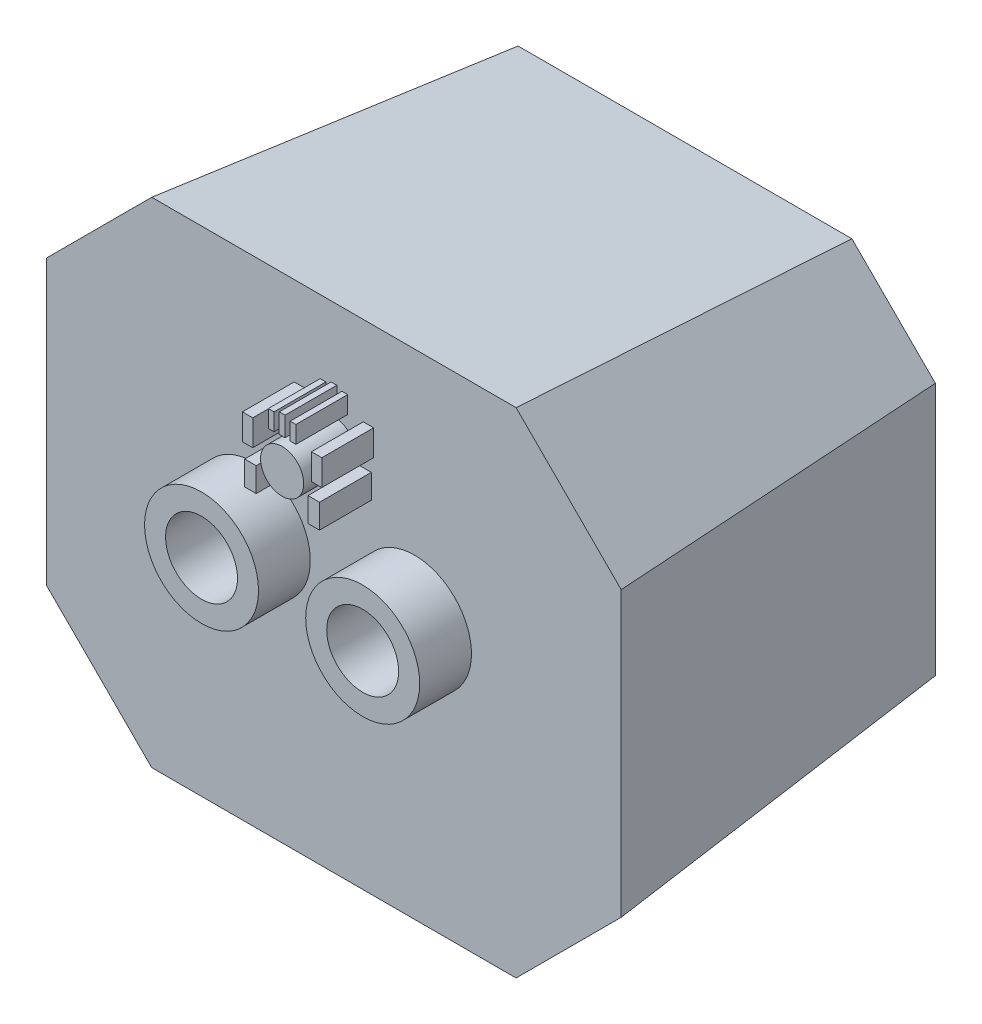
SolidWorks part; units mm, degrees
ref_plane "Front Plane" through (0, 0, 0) normal (0, 0, 1) x (1, 0, 0)
ref_plane "Top Plane" through (0, 0, 0) normal (0, 1, 0) x (1, 0, 0)
ref_plane "Right Plane" through (0, 0, 0) normal (1, 0, 0) x (0, 0, -1)
sketch "Sketch1" plane through (0, 0, 0) normal (0, 0, 1) x (1, 0, 0)
  line L0 (-58, 73) -> (58, 73)
  line L1 (58, 73) -> (87, 44)
  line L2 (87, 44) -> (87, -44)
  line L3 (87, -44) -> (58, -73)
  line L4 (58, -73) -> (-58, -73)
  line L5 (-58, -73) -> (-87, -44)
  line L6 (-87, -44) -> (-87, 44)
  line L7 (-87, 44) -> (-58, 73)
  circle A0 centre (-28, 4) radius 12.5
  circle A1 centre (28, 4) radius 12.5
extrude "Boss-Extrude1" add sketch "Sketch1" along normal blind 122 draft 6 draft outward yes
sketch "Sketch2" plane through (0, 0, 0) normal (0, 0, 1) x (1, 0, 0)
  line L1 (-4.8, 54.5) -> (-2.8, 54.5)
  line L2 (-4.8, 54.5) -> (-4.8, 60.5)
  line L3 (-4.8, 60.5) -> (-2.8, 60.5)
  line L4 (-2.8, 54.5) -> (-2.8, 60.5)
  line L6 (-1, 54.6) -> (1, 54.6)
  line L7 (-1, 54.6) -> (-1, 61.4)
  line L8 (-1, 61.4) -> (1, 61.4)
  line L9 (1, 54.6) -> (1, 61.4)
  line L11 (2.8, 54.5) -> (4.8, 54.5)
  line L12 (2.8, 54.5) -> (2.8, 60.5)
  line L13 (2.8, 60.5) -> (4.8, 60.5)
  line L14 (4.8, 54.5) -> (4.8, 60.5)
  line L16 (-13.8, 46) -> (-10.2, 46)
  line L17 (-13.8, 46) -> (-13.8, 55)
  line L18 (-13.8, 55) -> (-10.2, 55)
  line L19 (-10.2, 46) -> (-10.2, 55)
  line L21 (10.2, 46) -> (13.8, 46)
  line L22 (10.2, 46) -> (10.2, 55)
  line L23 (10.2, 55) -> (13.8, 55)
  line L24 (13.8, 46) -> (13.8, 55)
  line L26 (-13, 32.8) -> (-9, 32.8)
  line L27 (-13, 32.8) -> (-13, 41.2)
  line L28 (-13, 41.2) -> (-9, 41.2)
  line L29 (-9, 32.8) -> (-9, 41.2)
  line L31 (9, 32.8) -> (13, 32.8)
  line L32 (9, 32.8) -> (9, 41.2)
  line L33 (9, 41.2) -> (13, 41.2)
  line L34 (13, 32.8) -> (13, 41.2)
  circle A0 centre (-28, 4) radius 19.8
  circle A1 centre (-28, 4) radius 12.5
  circle A2 centre (28, 4) radius 19.8
  circle A3 centre (28, 4) radius 12.5
  circle A4 centre (0, 44) radius 7.5
extrude "Boss-Extrude2" add sketch "Sketch2" along normal blind 140
